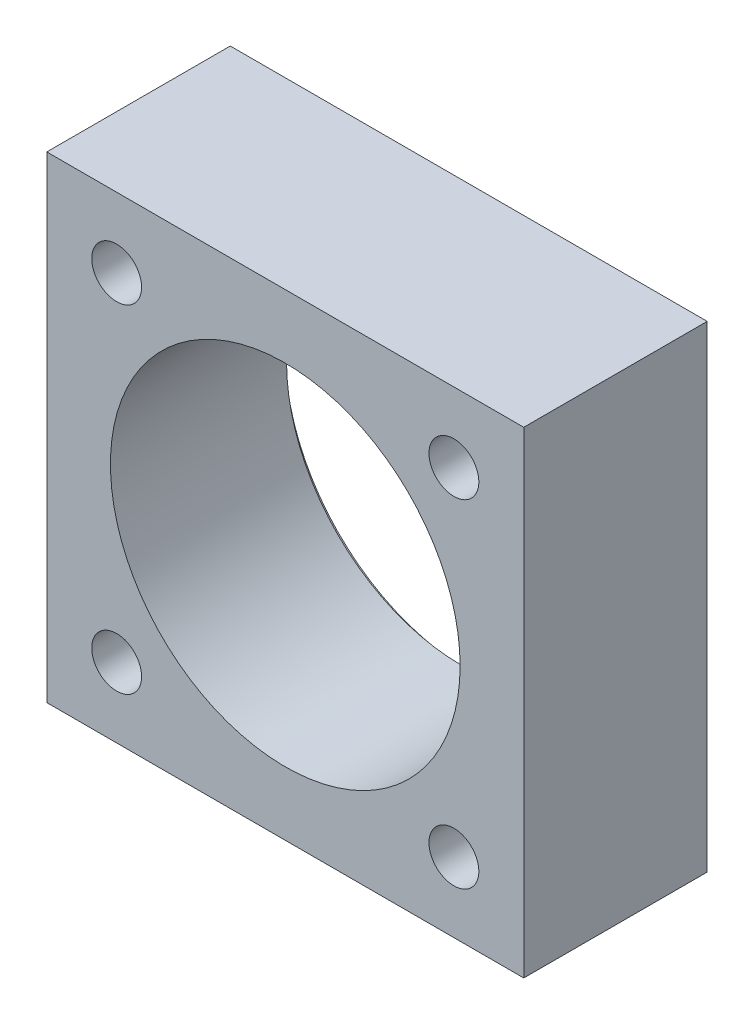
SolidWorks part; units mm, degrees
ref_plane "Front Plane" through (0, 0, 0) normal (0, 0, 1) x (1, 0, 0)
ref_plane "Top Plane" through (0, 0, 0) normal (0, 1, 0) x (1, 0, 0)
ref_plane "Right Plane" through (0, 0, 0) normal (1, 0, 0) x (0, 0, -1)
sketch "Sketch2" plane through (0, 0, 0) normal (0, 0, 1) x (1, 0, 0)
  line L1 (-16.51, 16.51) -> (16.51, 16.51)
  line L2 (-16.51, 16.51) -> (-16.51, -16.51)
  line L3 (-16.51, -16.51) -> (16.51, -16.51)
  line L4 (16.51, 16.51) -> (16.51, -16.51)
  line L5 (-16.51, 16.51) -> (16.51, -16.51) construction
  line L6 (-16.51, -16.51) -> (16.51, 16.51) construction
  point P0 (0, 0)
  dimension "D1" = 33.02
extrude "Boss-Extrude1" add sketch "Sketch2" along normal blind 12.7
sketch "Sketch3" plane through (0, 0, 12.7) normal (0, 0, 1) x (1, 0, 0)
  circle A0 centre (0, 0) radius 12.1044
  dimension "D1" = 24.2087
extrude "Cut-Extrude1" cut sketch "Sketch3" against normal through all
sketch "Sketch4" plane through (0, 0, 12.7) normal (0, 0, 1) x (1, 0, 0)
  circle A0 centre (0, 0) radius 12.7
  dimension "D1" = 25.4
hole_wizard "#8-32 Tapped Hole1" positions "Sketch8" profile "Sketch7" tap size "#8-32" standard "ANSI Inch" end condition through all
sketch "Sketch8" plane through (0, 0, 12.7) normal (0, 0, 1) x (1, 0, 0)
  line L0 (-16.51, 16.51) -> (0, 0) construction
  point P6 (-11.6743, 11.6743)
  point P12 (11.6743, 11.6743)
  point P13 (11.6743, -11.6743)
  point P14 (-11.6743, -11.6743)
  dimension "D2" = 16.51
  dimension "D1" = 4
cosmetic thread "Hole Thread1" parameters "D2"=4.1656
cosmetic thread "Hole Thread2" parameters "D2"=4.1656
cosmetic thread "Hole Thread3" parameters "D2"=4.1656
cosmetic thread "Hole Thread4" parameters "D2"=4.1656
sketch "Sketch7" plane through (-11.6743, 11.6743, 12.7) normal (1, 0, 0) x (0, -1, 0)
  line L0 (0, 0) -> (0, 12.7)
  line L1 (0, 12.7) -> (1.7272, 12.7)
  line L2 (1.7272, 12.7) -> (1.7272, 0)
  line L5 (1.7272, 0) -> (0, 0)
  line L11 (0, -6.35) -> (0, 107.95) construction
  dimension "Thru Tap Drill Dia." = 3.4544
  dimension "Thru Tap Drill Depth" = 12.7
sketch "Sketch9" plane through (0, 0, 0) normal (0, 0, -1) x (-1, 0, 0)
  circle A0 centre (0, 0) radius 12.7
  dimension "D1" = 25.4
extrude "Cut-Extrude2" cut sketch "Sketch9" against normal blind 0.508
